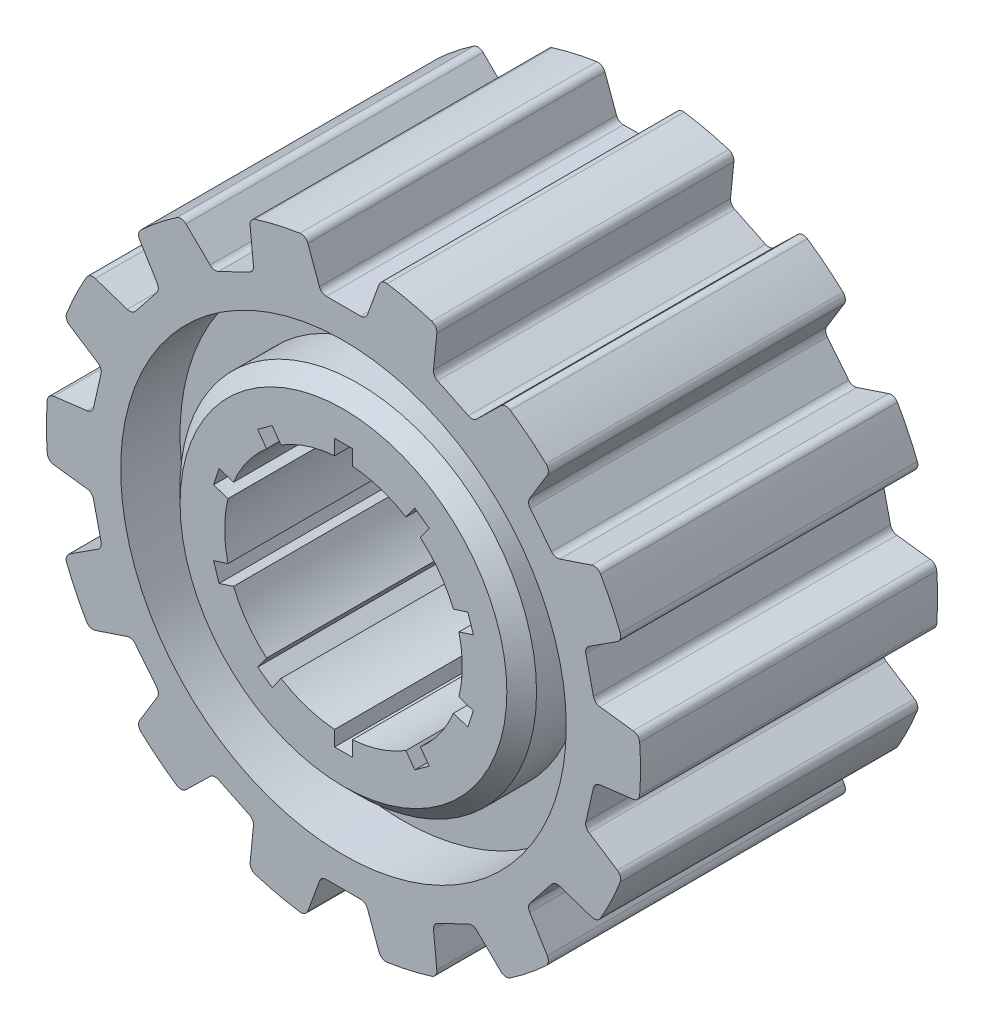
SolidWorks part; units mm, degrees
ref_plane "Front Plane" through (0, 0, 0) normal (0, 0, 1) x (1, 0, 0)
ref_plane "Top Plane" through (0, 0, 0) normal (0, 1, 0) x (1, 0, 0)
ref_plane "Right Plane" through (0, 0, 0) normal (1, 0, 0) x (0, 0, -1)
sketch "Sketch1" plane through (0, 0, 0) normal (0, 0, 1) x (1, 0, 0)
  line L0 (0, 0) -> (0, 8.4138) construction
  line L1 (2.4023, 3.8169) -> (2.1018, 3.4033)
  line L2 (-0.3, 4.5) -> (0.3, 4.5)
  line L3 (-0.3, 4.5) -> (-0.3, 3.9887)
  line L5 (0.3, 4.5) -> (0.3, 3.9887)
  line L6 (2.4023, 3.8169) -> (2.8877, 3.4642)
  line L7 (2.8877, 3.4642) -> (2.5872, 3.0506)
  line L8 (4.187, 1.6759) -> (3.7008, 1.5179)
  line L9 (4.187, 1.6759) -> (4.3725, 1.1053)
  line L10 (4.3725, 1.1053) -> (3.8862, 0.9473)
  line L11 (4.3725, -1.1053) -> (3.8862, -0.9473)
  line L12 (4.3725, -1.1053) -> (4.187, -1.6759)
  line L13 (4.187, -1.6759) -> (3.7008, -1.5179)
  line L14 (2.8877, -3.4642) -> (2.5872, -3.0506)
  line L15 (2.8877, -3.4642) -> (2.4023, -3.8169)
  line L16 (2.4023, -3.8169) -> (2.1018, -3.4033)
  line L17 (0.3, -4.5) -> (0.3, -3.9887)
  line L18 (0.3, -4.5) -> (-0.3, -4.5)
  line L19 (-0.3, -4.5) -> (-0.3, -3.9887)
  line L20 (-2.4023, -3.8169) -> (-2.1018, -3.4033)
  line L21 (-2.4023, -3.8169) -> (-2.8877, -3.4642)
  line L22 (-2.8877, -3.4642) -> (-2.5872, -3.0506)
  line L23 (-4.187, -1.6759) -> (-3.7008, -1.5179)
  line L24 (-4.187, -1.6759) -> (-4.3725, -1.1053)
  line L25 (-4.3725, -1.1053) -> (-3.8862, -0.9473)
  line L26 (-4.3725, 1.1053) -> (-3.8862, 0.9473)
  line L27 (-4.3725, 1.1053) -> (-4.187, 1.6759)
  line L28 (-4.187, 1.6759) -> (-3.7008, 1.5179)
  line L29 (-2.8877, 3.4642) -> (-2.5872, 3.0506)
  line L30 (-2.8877, 3.4642) -> (-2.4023, 3.8169)
  line L31 (-2.4023, 3.8169) -> (-2.1018, 3.4033)
  circle A0 centre (0, 0) radius 10
  arc A1 (-0.3, 3.9887) -> (-2.1018, 3.4033) centre (0, 0) ccw
  arc A2 (-2.5872, 3.0506) -> (-3.7008, 1.5179) centre (0, 0) ccw
  arc A3 (-3.8862, 0.9473) -> (-3.8862, -0.9473) centre (0, 0) ccw
  arc A4 (-3.7008, -1.5179) -> (-2.5872, -3.0506) centre (0, 0) ccw
  arc A5 (-2.1018, -3.4033) -> (-0.3, -3.9887) centre (0, 0) ccw
  arc A6 (0.3, -3.9887) -> (2.1018, -3.4033) centre (0, 0) ccw
  arc A7 (2.5872, -3.0506) -> (3.7008, -1.5179) centre (0, 0) ccw
  arc A8 (3.8862, -0.9473) -> (3.8862, 0.9473) centre (0, 0) ccw
  arc A9 (3.7008, 1.5179) -> (2.5872, 3.0506) centre (0, 0) ccw
  arc A10 (2.1018, 3.4033) -> (0.3, 3.9887) centre (0, 0) ccw
  point P47 (0, 0)
  dimension "D1" = 20
  dimension "D2" = 8
  dimension "D3" = 0.6
  dimension "D4" = 4.5
  dimension "D5" = 10
extrude "Boss-Extrude1" add sketch "Sketch1" along normal mid plane 10
sketch "Sketch2" plane through (0, 0, 5) normal (0, 0, 1) x (1, 0, 0)
  line L0 (0, 0) -> (0, 10) construction
  line L1 (-0.75, 8.5) -> (0.75, 8.5)
  line L2 (0.75, 8.5) -> (1.2666, 9.9195)
  line L3 (-0.75, 8.5) -> (-1.2666, 9.9195)
  circle A0 centre (0, 0) radius 10 construction
  circle M5 centre (0, 0) radius 10
  dimension "D1" = 1.5
  dimension "D2" = 20
  dimension "D3" = 8.5
extrude "Cut-Extrude2" cut sketch "Sketch2" against normal blind 10 and the other way through all contours L0 L1 L2 M5 | L1 L0 L3 M5
pattern_circular "CirPattern1" count 14 over 360 about axis through (0, 0, 0) along (0, 0, 1) of "Cut-Extrude2"
sketch "Sketch3" plane through (0, 0, 5) normal (0, 0, 1) x (1, 0, 0)
  circle A0 centre (0, 0) radius 7.5
  circle A1 centre (0, 0) radius 6
  dimension "D1" = 15
  dimension "D2" = 12
extrude "Cut-Extrude3" cut sketch "Sketch3" against normal blind 2
mirror "Mirror1" about plane through (0, 0, 0) normal (0, 0, 1) of "Cut-Extrude3"
chamfer "Chamfer1" distance 0.5 angle 45 2 edges at (6, 0, -5) (6, 0, 5)
fillet "Fillet1" radius 0.25 56 edges at (-7.1132, 4.7133, 0) (-6.178, 5.886, 0) (-6.9656, 7.175, 0) (-4.3637, 7.3328, 0) (-3.0123, 7.9836, 0) (-3.1627, 9.4867, 0) (-0.75, 8.5, 0) (0.75, 8.5, 0) (3.1627, 9.4867, 0) (3.0123, 7.9836, 0) (4.3637, 7.3328, 0) (5.4451, 8.3875, 0) (6.9656, 7.175, 0) (6.178, 5.886, 0) (7.1132, 4.7133, 0) (8.5451, 5.1944, 0) (9.3889, 3.4422, 0) (8.12, 2.6226, 0) (8.4538, 1.1602, 0) (9.9526, 0.9724, 0) (9.9526, -0.9724, 0) (8.4538, -1.1602, 0) (8.12, -2.6226, 0) (9.3889, -3.4422, 0) (8.5451, -5.1944, 0) (7.1132, -4.7133, 0) (6.178, -5.886, 0) (6.9656, -7.175, 0) (5.4451, -8.3875, 0) (4.3637, -7.3328, 0) (3.0123, -7.9836, 0) (3.1627, -9.4867, 0) (1.2666, -9.9195, 0) (0.75, -8.5, 0) (-0.75, -8.5, 0) (-1.2666, -9.9195, 0) (-3.1627, -9.4867, 0) (-3.0123, -7.9836, 0) (-4.3637, -7.3328, 0) (-5.4451, -8.3875, 0) (-6.9656, -7.175, 0) (-6.178, -5.886, 0) (-7.1132, -4.7133, 0) (-8.5451, -5.1944, 0) (-9.3889, -3.4422, 0) (-8.12, -2.6226, 0) (-8.4538, -1.1602, 0) (-9.9526, -0.9724, 0) (-9.9526, 0.9724, 0) (-8.4538, 1.1602, 0) (-8.12, 2.6226, 0) (-9.3889, 3.4422, 0) (-8.5451, 5.1944, 0) (-5.4451, 8.3875, 0)
